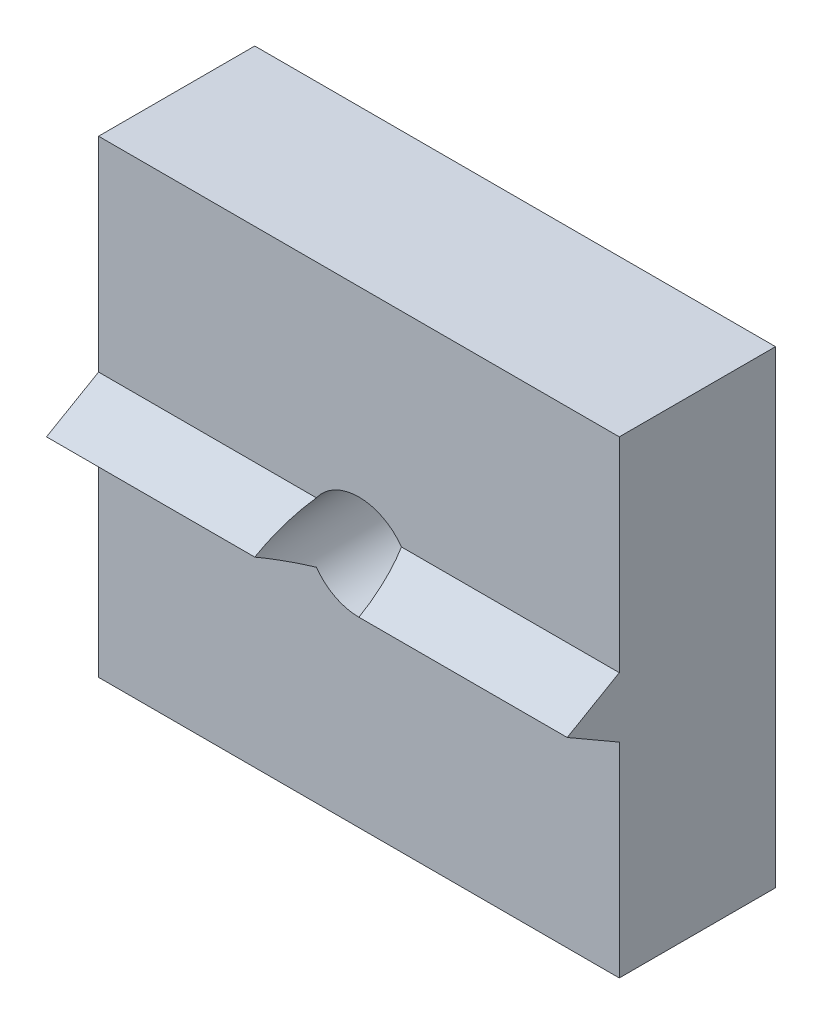
SolidWorks part; units mm, degrees
ref_plane "Front Plane" through (0, 0, 0) normal (0, 0, 1) x (1, 0, 0)
ref_plane "Top Plane" through (0, 0, 0) normal (0, 1, 0) x (1, 0, 0)
ref_plane "Right Plane" through (0, 0, 0) normal (1, 0, 0) x (0, 0, -1)
sketch "Sketch1" plane through (0, 0, 0) normal (0, 0, 1) x (1, 0, 0)
  line L0 (-5, -4.5) -> (5, 4.5) construction
  line L1 (-5, -4.5) -> (5, -4.5)
  line L2 (-5, -4.5) -> (-5, 4.5)
  line L3 (-5, 4.5) -> (5, 4.5)
  line L4 (5, -4.5) -> (5, 4.5)
  line L5 (5, -4.5) -> (-5, 4.5) construction
  point P4 (0, 0)
  dimension "D1" = 10
  dimension "D2" = 9
extrude "Boss-Extrude1" add sketch "Sketch1" along normal blind 3
sketch "Sketch2" plane through (5, 0, 0) normal (1, 0, 0) x (0, 0, -1)
  line L0 (-3, -4.5) -> (-3, 4.5) construction
  line L1 (-4, 0) -> (-2.5, -0.866)
  line L2 (-2.5, -0.866) -> (-2.5, 0.866)
  line L3 (-2.5, 0.866) -> (-4, 0)
  line L4 (-3, 0) -> (-4, 0) construction
  circle A0 centre (-3, 0) radius 0.5 construction
  dimension "D1" = 1
extrude "Boss-Extrude2" add sketch "Sketch2" against normal up to surface (10 mm away) up to face at (-5, 0, 1.5)
sketch "Sketch3" plane through (0, 0, 0) normal (0, 0, -1) x (-1, 0, 0)
  circle A0 centre (0, 0) radius 1
  dimension "D1" = 2
extrude "Cut-Extrude1" cut sketch "Sketch3" against normal up to next
